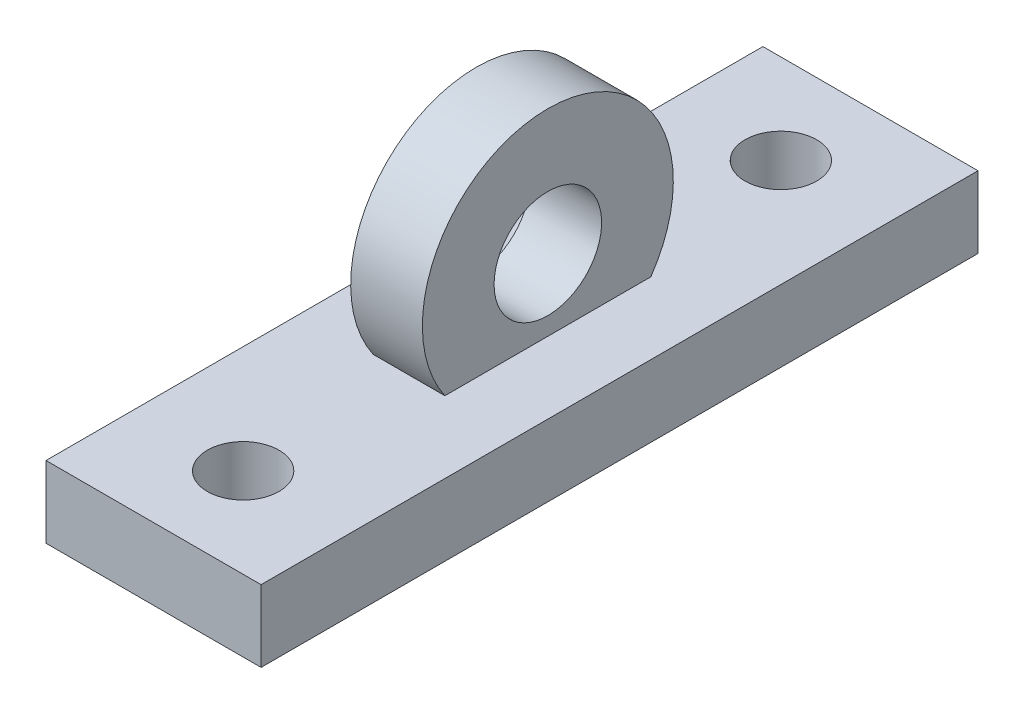
SolidWorks part; units mm, degrees
other "标注1"
sketch "草图3" plane through (-22.25, 4, -10) normal (-0.231, 0.6469, -0.7268) x (-0.9696, -0.2151, 0.1167)
ref_plane "前视基准面" through (0, 0, 0) normal (0, 0, 1) x (1, 0, 0)
ref_plane "上视基准面" through (0, 0, 0) normal (0, 1, 0) x (1, 0, 0)
ref_plane "右视基准面" through (0, 0, 0) normal (1, 0, 0) x (0, 0, -1)
other "Configuration Table"
sketch "草图4" plane through (0, 0, 0) normal (0, 1, 0) x (1, 0, 0)
  line L1 (-3, -10) -> (3, -10)
  line L2 (-3, -10) -> (-3, 10)
  line L3 (-3, 10) -> (3, 10)
  line L4 (3, -10) -> (3, 10)
  line L5 (-3, -10) -> (3, 10) construction
  line L6 (-3, 10) -> (3, -10) construction
  point P0 (0, 0)
  dimension "D1" = 20
  dimension "D2" = 6
extrude "凸台-拉伸1" add sketch "草图4" along normal blind 2
sketch "草图6" plane through (-3, 0, 0) normal (-1, 0, 0) x (0, 0, 1)
  line L2 (-10, 2) -> (10, 2) construction
  circle A0 centre (0, 4) radius 1.5
  circle A1 centre (0, 4) radius 3.5
  dimension "D1" = 3
  dimension "D2" = 2
  dimension "D3" = 2
extrude "凸台-拉伸3" add sketch "草图6" against normal blind 2 from offset 2 offset against normal yes
sketch "草图7" plane through (0, 2, 0) normal (0, 1, 0) x (1, 0, 0)
  line L0 (0, -7.5) -> (0, 7.5)
  line L1 (-3, -10) -> (3, -10) construction
  circle A0 centre (0, -7.5) radius 1
  circle A1 centre (0, 7.5) radius 1.5
  circle A2 centre (0, 7.5) radius 1
  circle A3 centre (0, -7.5) radius 1.5
  dimension "D1" = 2
  dimension "D2" = 3
  dimension "D3" = 2.5
extrude "切除-拉伸1" cut sketch "草图7" against normal through all contours A0 | A2
